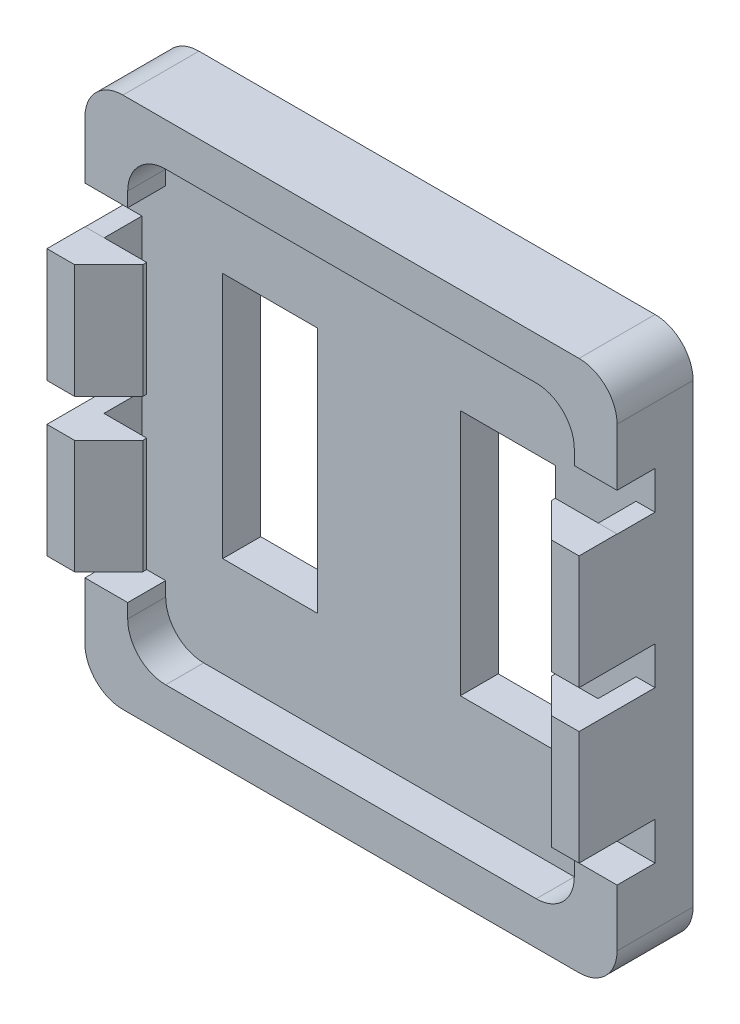
SolidWorks part; units mm, degrees
ref_plane "Plan de face" through (0, 0, 0) normal (0, 0, 1) x (1, 0, 0)
ref_plane "Plan de dessus" through (0, 0, 0) normal (0, 1, 0) x (1, 0, 0)
ref_plane "Plan de droite" through (0, 0, 0) normal (1, 0, 0) x (0, 0, -1)
sketch "Esquisse1" plane through (0, 0, 0) normal (0, 0, 1) x (1, 0, 0)
  line L1 (12, -14) -> (-12, -14)
  line L2 (14, -12) -> (14, 12)
  line L3 (12, 14) -> (-12, 14)
  line L4 (-14, -12) -> (-14, 12)
  line L5 (14, -14) -> (-14, 14) construction
  line L6 (14, 14) -> (-14, -14) construction
  arc A0 (-12, -14) -> (-14, -12) centre (-12, -12) cw
  arc A1 (12, -14) -> (14, -12) centre (12, -12) ccw
  arc A2 (14, 12) -> (12, 14) centre (12, 12) ccw
  arc A3 (-12, 14) -> (-14, 12) centre (-12, 12) ccw
  point P0 (0, 0)
  dimension "D2" = 2
  dimension "D1" = 28
extrude "Boss.-Extru.1" add sketch "Esquisse1" along normal blind 4
sketch "Esquisse2" plane through (0, 0, 4) normal (0, 0, 1) x (1, 0, 0)
  line L0 (-14, 12) -> (-14, -12) construction
  line L1 (-9.75, -11.75) -> (9.75, -11.75)
  line L2 (-11.75, -9.75) -> (-11.75, -9)
  line L3 (-9.75, 11.75) -> (9.75, 11.75)
  line L4 (11.75, -9.75) -> (11.75, -9)
  line L5 (-11.75, -11.75) -> (11.75, 11.75) construction
  line L6 (-11.75, 11.75) -> (11.75, -11.75) construction
  line L7 (-14, 8.9885) -> (-11.75, 8.9885)
  line L8 (-14, 8.9885) -> (-14, 6.9885)
  line L11 (-1000, -0.0058) -> (49000, -0.0058) construction
  line L14 (-14, -9) -> (-11.75, -9)
  line L15 (-14, -9) -> (-14, -7)
  line L16 (-11.75, 8.9885) -> (-11.75, 9.75)
  line L18 (-14, 6.9885) -> (-13, 6.9885)
  line L19 (-13, 6.9885) -> (-13, 0.9942)
  line L20 (-13, -7) -> (-14, -7)
  line L21 (0, -1000) -> (0, 49000) construction
  line L22 (14, 8.9885) -> (11.75, 8.9885)
  line L23 (14, 8.9885) -> (14, 6.9885)
  line L24 (14, 6.9885) -> (13, 6.9885)
  line L25 (13, 6.9885) -> (13, 0.9942)
  line L26 (13, -7) -> (14, -7)
  line L27 (14, -9) -> (14, -7)
  line L28 (14, -9) -> (11.75, -9)
  line L29 (11.75, 8.9885) -> (11.75, 9.75)
  line L30 (-13, -1.0058) -> (-13, -7)
  line L31 (-13, 0.9942) -> (-14, 0.9942)
  line L33 (-13, -1.0058) -> (-14, -1.0058)
  line L34 (-14, 0.9942) -> (-14, -1.0058)
  line L35 (13, -1.0058) -> (14, -1.0058)
  line L36 (14, 0.9942) -> (14, -1.0058)
  line L37 (13, 0.9942) -> (14, 0.9942)
  line L38 (13, -1.0058) -> (13, -7)
  arc A0 (-9.75, -11.75) -> (-11.75, -9.75) centre (-9.75, -9.75) cw
  arc A1 (9.75, -11.75) -> (11.75, -9.75) centre (9.75, -9.75) ccw
  arc A2 (9.75, 11.75) -> (11.75, 9.75) centre (9.75, 9.75) cw
  arc A3 (-11.75, 9.75) -> (-9.75, 11.75) centre (-9.75, 9.75) cw
  point P0 (0, 0)
  point P29 (0, -0.0058)
  dimension "D3" = 2
  dimension "D1" = 23.5
  dimension "D2" = 23.5
  dimension "D8" = 1
  dimension "D9" = 2
  dimension "D10" = 2
  dimension "D11" = 1
extrude "Enlèv. mat.-Extru.1" cut sketch "Esquisse2" against normal blind 2
sketch "Esquisse3" plane through (0, 0, 2) normal (0, 0, 1) x (1, 0, 0)
  line L5 (-1000, 0) -> (49000, 0) construction
  line L6 (-11.75, -9) -> (-11.75, -9.75) construction
  line L7 (-3.75, -6.5) -> (-8.75, -6.5)
  line L8 (-3.75, -6.5) -> (-3.75, 6.5)
  line L9 (-3.75, 6.5) -> (-8.75, 6.5)
  line L10 (-8.75, -6.5) -> (-8.75, 6.5)
  line L11 (-3.75, -6.5) -> (-8.75, 6.5) construction
  line L12 (-3.75, 6.5) -> (-8.75, -6.5) construction
  line L13 (0, -1000) -> (0, 49000) construction
  line L14 (3.75, 6.5) -> (8.75, 6.5)
  line L15 (8.75, -6.5) -> (8.75, 6.5)
  line L16 (3.75, -6.5) -> (8.75, -6.5)
  line L17 (3.75, -6.5) -> (3.75, 6.5)
  point P0 (-6.25, 0)
  dimension "D1" = 13
  dimension "D2" = 5
  dimension "D3" = 5.5
extrude "Enlèv. mat.-Extru.2" cut sketch "Esquisse3" against normal through all
sketch "Esquisse4" plane through (0, 0, 4) normal (0, 0, 1) x (1, 0, 0)
  line L0 (-10.75, -1.0058) -> (-10.75, -7)
  line L5 (-11.75, -9) -> (-11.75, -9.75) construction
  line L6 (-14, 7) -> (-10.75, 7)
  line L7 (-14, 7) -> (-14, 0.9942)
  line L8 (-14, -7) -> (-10.75, -7)
  line L9 (-10.75, 7) -> (-10.75, 0.9942)
  line L10 (-14, 12) -> (-14, 8.9885) construction
  line L11 (-14, 0.9942) -> (-10.75, 0.9942)
  line L13 (-14, -1.0058) -> (-10.75, -1.0058)
  line L15 (-14, -1.0058) -> (-14, -7)
  dimension "D1" = 1
  dimension "D2" = 14
  dimension "D3" = 7
  dimension "D4" = 2
extrude "Boss.-Extru.2" add sketch "Esquisse4" along normal blind 2
chamfer "Chanfrein3" distance 1.8 angle 45 2 edges at (-10.75, -4.0029, 6) (-10.75, 3.9971, 6)
mirror "Symétrie1" about plane through (0, 0, 0) normal (1, 0, 0) of "Chanfrein3", "Boss.-Extru.2"
